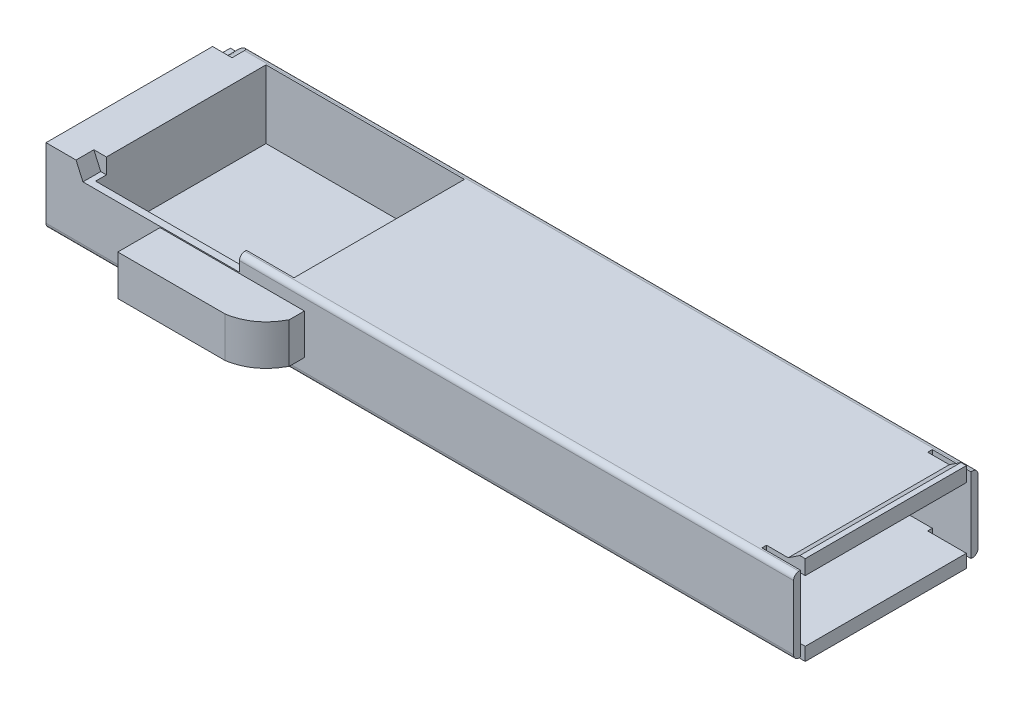
SolidWorks part; units mm, degrees
ref_plane "前视基准面" through (0, 0, 0) normal (0, 0, 1) x (1, 0, 0)
ref_plane "上视基准面" through (0, 0, 0) normal (0, 1, 0) x (1, 0, 0)
ref_plane "右视基准面" through (0, 0, 0) normal (1, 0, 0) x (0, 0, -1)
other "Configuration Table"
sketch "草图1" plane through (0, 0, 0) normal (1, 0, 0) x (0, 0, -1)
  line L0 (-11.9, 4.85) -> (-11.9, -4.85)
  line L1 (-11, 3.95) -> (11, 3.95)
  line L2 (-11, 3.95) -> (-11, -3.95)
  line L3 (-11, -3.95) -> (11, -3.95)
  line L4 (11, 3.95) -> (11, -3.95)
  line L5 (-11, 3.95) -> (11, -3.95) construction
  line L6 (-11, -3.95) -> (11, 3.95) construction
  line L7 (-11.9, -4.85) -> (11.9, -4.85)
  line L8 (11.9, 4.85) -> (11.9, -4.85)
  line L9 (-11.9, 4.85) -> (11.9, 4.85)
  line L10 (55, 0) -> (-55, 0) construction
  point P0 (0, 0)
  dimension "D1" = 7.9
  dimension "D2" = 22
  dimension "D3" = 0.9
extrude "凸台-拉伸1" add sketch "草图1" along normal blind 93.5
sketch "草图3" plane through (0, 0, 11.9) normal (0, 0, 1) x (1, 0, 0)
  line L0 (3.6643, 3.3873) -> (3.6643, 4.85)
  line L1 (93.5, 4.85) -> (0, 4.85) construction
  line L2 (5.6643, 3.3873) -> (5.6643, 4.85)
  line L3 (5.6643, 4.85) -> (3.6643, 4.85)
  line L5 (-3.2135, 0) -> (147.8577, 0)
  line L6 (-3.2135, 0) -> (-3.2135, 8.5216)
  line L7 (-3.2135, 8.5216) -> (147.8577, 8.5216)
  line L8 (147.8577, 0) -> (147.8577, 8.5216)
  arc A0 (3.6643, 3.3873) -> (5.6643, 3.3873) centre (4.6643, 3.3873) ccw
  dimension "D1" = 2
sketch "草图4" plane through (0, 0, 0) normal (-1, 0, 0) x (0, 0, 1)
  line L0 (0, -55) -> (0, 55) construction
  line L5 (11.9, 9.0004) -> (14.4, 9.0004)
  line L6 (-11.9, -4.85) -> (-14.4, -4.85)
  line L7 (14.4, -4.85) -> (14.4, 9.0004)
  line L8 (-11.9, -4.85) -> (-11.9, 9.0004)
  line L9 (-11.9, 9.0004) -> (-14.4, 9.0004)
  line L10 (-14.4, -4.85) -> (-14.4, 9.0004)
  line L11 (11.9, -4.85) -> (14.4, -4.85)
  line L12 (11.9, -4.85) -> (11.9, 9.0004)
  dimension "D1" = 2.5
sketch "草图5" plane through (0, 4.85, 0) normal (0, 1, 0) x (1, 0, 0)
  line L6 (-2.7513, 11) -> (28.1108, 11)
  line L7 (-2.7513, 11) -> (-2.7513, -11)
  line L8 (-2.7513, -11) -> (28.1108, -11)
  line L9 (28.1108, 11) -> (28.1108, -11)
  line L10 (-2.7513, 11) -> (28.1108, -11) construction
  line L11 (-2.7513, -11) -> (28.1108, 11) construction
  point P0 (12.6798, 0)
  dimension "D1" = 22
extrude "切除-拉伸1" cut sketch "草图5" against normal blind 5
sketch "草图7" plane through (0, 0, 0) normal (-1, 0, 0) x (0, 0, 1)
  line L0 (-11, 4.85) -> (11, 4.85)
  line L8 (11.9, 4.85) -> (11, 4.85)
  line L9 (11, 4.85) -> (11, -3.95)
  line L10 (11, -3.95) -> (-11, -3.95)
  line L11 (-11, -3.95) -> (-11, 4.85)
  line L12 (-11, 4.85) -> (-11.9, 4.85)
  line L13 (-11.9, 4.85) -> (-11.9, -4.85)
  line L14 (-11.9, -4.85) -> (11.9, -4.85)
  line L15 (11.9, -4.85) -> (11.9, 4.85)
  line L16 (11.9, 4.85) -> (11, 4.85)
  line L20 (-11, 4.85) -> (-11.9, 4.85)
  line L21 (-11.9, 4.85) -> (-11.9, -4.85)
  line L22 (-11.9, -4.85) -> (11.9, -4.85)
  line L23 (11.9, -4.85) -> (11.9, 4.85)
  dimension "D1" = 0
extrude "凸台-拉伸3" add sketch "草图7" along normal blind 3 and the other way blind 2.5
sketch "草图8" plane through (0, 0, 11.9) normal (0, 0, 1) x (1, 0, 0)
  line L0 (0.8788, 4.85) -> (1.7665, 2.85)
  line L1 (93.5, 4.85) -> (-3, 4.85) construction
  line L3 (1.7665, 2.85) -> (21.9689, 2.85)
  line L4 (21.9689, 2.85) -> (21.9689, 4.85)
  line L5 (0.8788, 4.85) -> (21.9689, 4.85)
  dimension "D1" = 2
extrude "切除-拉伸2" cut sketch "草图8" against normal blind 2.3
sketch "草图9" plane through (0, 0, -11.9) normal (0, 0, -1) x (-1, 0, 0)
  line L0 (-93.5, 4.85) -> (3, 4.85) construction
  line L1 (2.3473, 3.5165) -> (3, 3.5165)
  line L2 (3, 4.85) -> (3, -4.85) construction
  line L3 (0.4837, 4.85) -> (3, 4.85)
  line L4 (3, 4.85) -> (3, 3.5165)
  spline S0 degree 2 poles (0.4837, 4.85) (1.5705, 4.4095) (2.3473, 3.5165) knots 0 0 0 1 1 1
extrude "切除-拉伸3" cut sketch "草图9" against normal blind 2.3
sketch "草图10" plane through (0, 0, 11.9) normal (0, 0, 1) x (1, 0, 0)
  line L1 (3.334, 2.7103) -> (30.7485, 2.7103)
  line L2 (3.334, 2.7103) -> (3.334, -2.4964)
  line L3 (3.334, -2.4964) -> (30.7485, -2.4964)
  line L4 (30.7485, 2.7103) -> (30.7485, -2.4964)
extrude "凸台-拉伸4" add sketch "草图10" along normal blind 5.45
sketch "草图11" plane through (0, 0, -11.9) normal (0, 0, -1) x (-1, 0, 0)
  line L0 (-93.5, -4.85) -> (-93.5, -5.65)
  line L1 (-93.5, -4.85) -> (-93.5, 4.85) construction
  line L2 (-93.5, -5.65) -> (-92.9, -5.65)
  line L3 (-92.9, -5.65) -> (-91.3, -4.85)
  line L4 (-93.5, -4.85) -> (3, -4.85) construction
  line L5 (-93.5, -4.85) -> (-91.3, -4.85)
  line L6 (-93.5, 4.85) -> (0.4837, 4.85) construction
  line L7 (-91.3, 4.85) -> (-92.8, 5.85)
  line L8 (-92.8, 5.85) -> (-93.5, 5.85)
  line L9 (-93.5, 5.85) -> (-93.5, 4.85)
  line L10 (-93.5, 4.85) -> (-91.3, 4.85)
  dimension "D1" = 1
  dimension "D2" = 0.8
  dimension "D3" = 0.6
  dimension "D4" = 0.7
  dimension "D5" = 1.5
extrude "凸台-拉伸5" add sketch "草图11" against normal up to surface (23.8 mm away) up to face at (28.4479, 1.925, 11.9)
sketch "草图12" plane through (0, 2.7103, 0) normal (0, 1, 0) x (1, 0, 0)
  line L0 (30.7485, -17.35) -> (3.334, -17.35) construction
  line L1 (30.3542, -13.8647) -> (30.3542, -11.9)
  line L2 (91.3, -11.9) -> (21.9689, -11.9) construction
  line L3 (30.3542, -11.9) -> (31.0293, -11.9)
  line L4 (31.0293, -11.9) -> (31.2739, -17.7296)
  line L5 (31.2739, -17.7296) -> (25.5597, -17.35)
  line L6 (11.7178, -17.35) -> (11.7178, -11.9)
  line L7 (11.7178, -11.9) -> (1.4304, -11.9)
  line L8 (1.4304, -11.9) -> (1.4304, -18.181)
  line L9 (1.4304, -18.181) -> (11.7178, -17.35)
  line L10 (30.7485, -11.9) -> (3.334, -11.9) construction
  spline S0 degree 2 poles (25.5597, -17.35) (28.7388, -16.8583) (30.3542, -13.8647) knots 0 0 0 1 1 1
extrude "切除-拉伸4" cut sketch "草图12" against normal blind 10
sketch "草图14" plane through (93.5, 0, 0) normal (1, 0, 0) x (0, 0, -1)
  line L1 (11, 4.85) -> (11, -3.95) construction
  line L3 (-11.9, 5.85) -> (11.9, 5.85) construction
  line L4 (-11, 5.85) -> (-11.9, 5.85)
  line L5 (-11.9, 5.85) -> (-11.9, -5.65) construction
  line L6 (-11.9, 5.85) -> (-11.9, 4.85)
  line L7 (-11.9, 4.85) -> (-11, 4.85)
  line L8 (-11.9, 4.85) -> (11.9, 4.85) construction
  line L9 (11.9, 5.85) -> (11, 5.85)
  line L10 (11.9, -5.65) -> (11.9, 5.85) construction
  line L14 (11, 4.85) -> (11.9, 4.85)
  line L15 (11.9, 4.85) -> (11.9, 5.85)
  line L16 (-11.9, -5.65) -> (11.9, -5.65) construction
  line L17 (11.9, -5.65) -> (11, -5.65)
  line L18 (11.9, -5.65) -> (11.9, -4.85)
  line L19 (11.9, -4.85) -> (11, -4.85)
  line L21 (-11.9, -4.85) -> (11.9, -4.85) construction
  line L22 (-11.9, -5.65) -> (-11, -5.65)
  line L23 (-11.9, -5.65) -> (-11.9, -4.85)
  line L24 (-11.9, -4.85) -> (-11, -4.85)
  line L28 (-10.4, -5.65) -> (-11, -5.65)
  line L29 (-10.4, -5.65) -> (-10.4, 5.85)
  line L30 (-10.4, 5.85) -> (-11, 5.85)
  line L31 (-11, -4.85) -> (-11, 4.85)
  line L32 (10.4, -5.65) -> (11, -5.65)
  line L33 (10.4, -5.65) -> (10.4, 5.85)
  line L34 (10.4, 5.85) -> (11, 5.85)
  line L35 (11, -4.85) -> (11, 4.85)
  dimension "D1" = 0.6
  dimension "D2" = 0.6
extrude "切除-拉伸5" cut sketch "草图14" against normal blind 5
fillet "圆角2" radius 0.7 4 edges at (46.5082, 4.85, -11.9) (45.25, -4.85, -11.9) (45.25, -4.85, 11.9) (57.7345, 4.85, 11.9)
equation "\".61.44725042mm\"=0"
